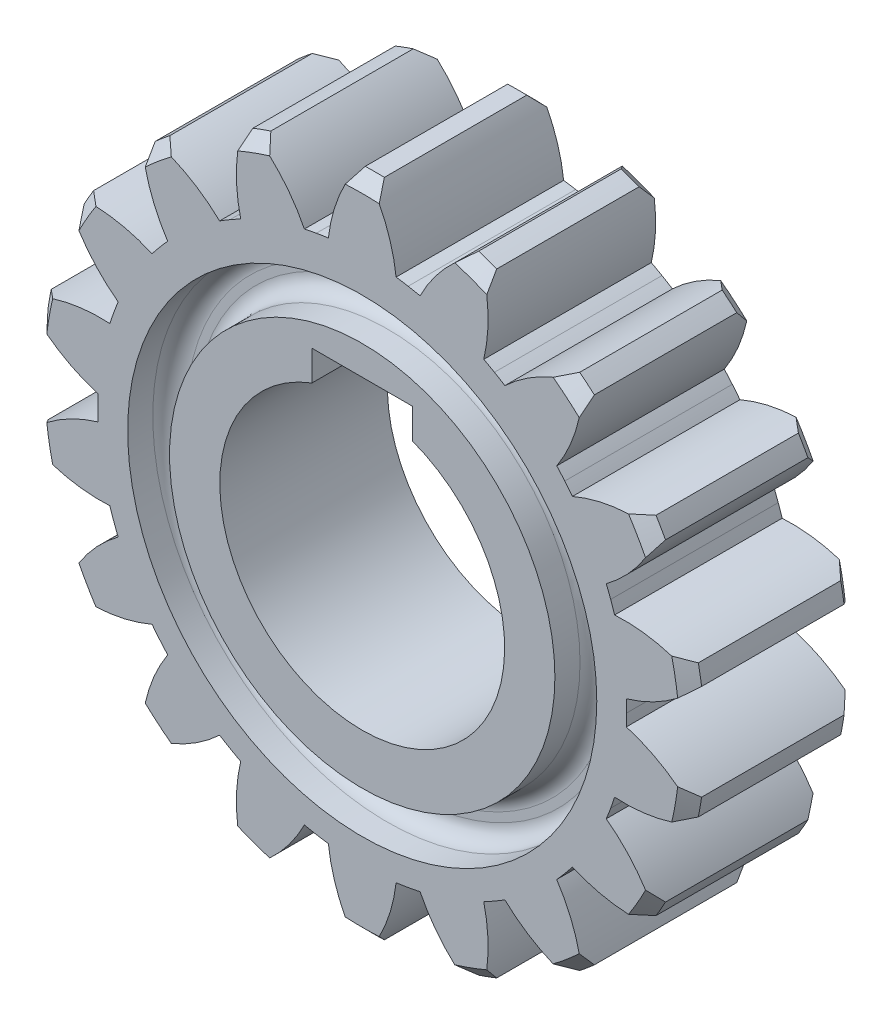
SolidWorks part; units mm, degrees
ref_plane "Front Plane" through (0, 0, 0) normal (0, 0, 1) x (1, 0, 0)
ref_plane "Top Plane" through (0, 0, 0) normal (0, 1, 0) x (1, 0, 0)
ref_plane "Right Plane" through (0, 0, 0) normal (1, 0, 0) x (0, 0, -1)
sketch "Sketch1" plane through (0, 0, 0) normal (0, 0, 1) x (1, 0, 0)
  line L0 (0, 35.0966) -> (0, -37.1453) construction
  line L1 (-45.7855, 0) -> (48.1573, 0) construction
  line L2 (-0.57, 31.4966) -> (-0.57, -32.7483) construction
  line L3 (-2.07, 30.4447) -> (-2.07, -32.7483) construction
  line L4 (-1.57, 30.4447) -> (-1.57, -32.7483) construction
  circle A0 centre (0, 0) radius 15.5
  circle A1 centre (0, 0) radius 18
  circle A2 centre (0, 0) radius 20
  arc A3 (-2.07, 15.3612) -> (-0.57, 19.9919) centre (7.394, 14.8538) cw
  arc A4 (2.07, 15.3612) -> (0.57, 19.9919) centre (-7.394, 14.8538) ccw
  point P15 (-2.07, 15.3612)
  point P16 (-0.57, 19.9919)
  point P17 (-1.57, 17.9314)
  dimension "D1" = 31
  dimension "D2" = 36
  dimension "D3" = 40
  dimension "D4" = 1.57
  dimension "D5" = 1
  dimension "D6" = 0.5
extrude "Boss-Extrude1" add sketch "Sketch1" along normal blind 10 contours A0 | A0 A4 A1 A3 | A1 A4 A2 A3
chamfer "Chamfer1" distance 0.75 angle 45 2 edges at (0, 20, 0) (0, 20, 10)
pattern_circular "CirPattern1" count 18 over 360 about axis through (0, 0.2842, 0) along (0, 0, 1) of "Boss-Extrude1", "Chamfer1"
sketch "Sketch2" plane through (0, 0, 10) normal (0, 0, 1) x (1, 0, 0)
  circle A0 centre (0, 0) radius 14
  circle A1 centre (0, 0) radius 11.5
  dimension "D1" = 28
  dimension "D2" = 23
extrude "Cut-Extrude1" cut sketch "Sketch2" against normal blind 2.5
fillet "Fillet1" radius 1 2 edges at (14, 0, 7.5) (11.5, 0, 7.5)
ref_plane "Plane1" through (0, 0, 5) normal (0, 0, 1) x (1, 0, 0)
mirror "Mirror1" about plane through (0, 0, 5) normal (0, 0, 1) of "Fillet1", "Cut-Extrude1"
sketch "Sketch3" plane through (0, 0, 10) normal (0, 0, 1) x (1, 0, 0)
  line L0 (0, 0) -> (0, 35.2065) construction
  line L1 (-3, 9.75) -> (3, 9.75)
  line L2 (-3, 9.75) -> (-3, 7.25)
  line L3 (-3, 7.25) -> (3, 7.25)
  line L4 (3, 9.75) -> (3, 7.25)
  line L5 (-29.4786, 8.5) -> (57.0056, 8.5) construction
  circle A0 centre (0, 0) radius 8.5
  dimension "D1" = 17
  dimension "D2" = 6
  dimension "D3" = 2.5
extrude "Cut-Extrude2" cut sketch "Sketch3" against normal up to next contours L2 A0 L4 L3 | A0 L4 L1 L2 | L4 A0 L2 L3
